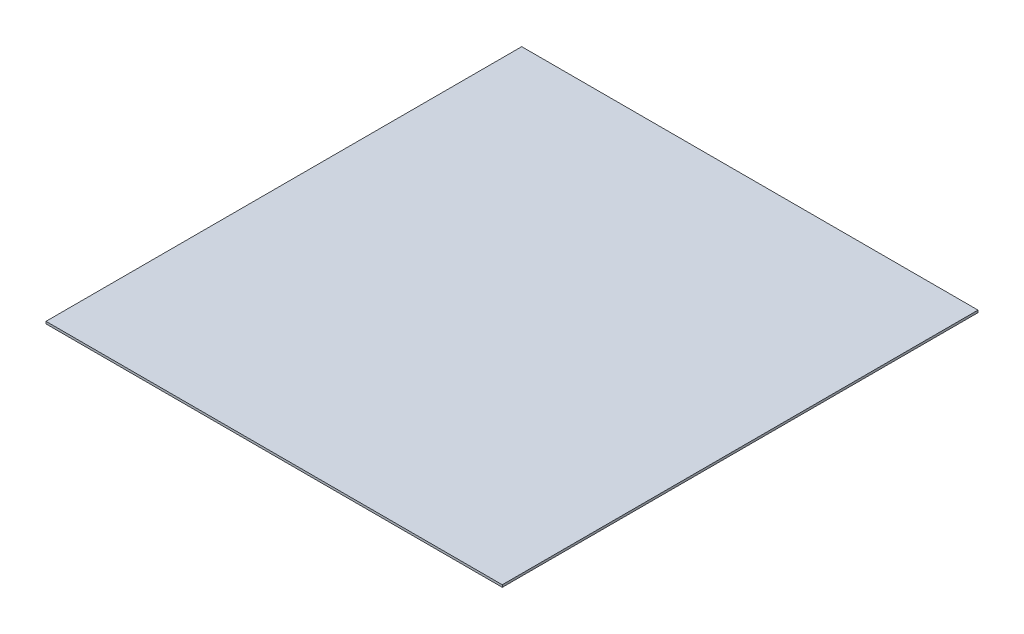
SolidWorks part; units mm, degrees
ref_plane "Front Plane" through (0, 0, 0) normal (0, 0, 1) x (1, 0, 0)
ref_plane "Top Plane" through (0, 0, 0) normal (0, 1, 0) x (1, 0, 0)
ref_plane "Right Plane" through (0, 0, 0) normal (1, 0, 0) x (0, 0, -1)
sketch "Sketch1" plane through (0, 0, 0) normal (0, 1, 0) x (1, 0, 0)
  line L1 (-176, 183.5) -> (176, 183.5)
  line L2 (-176, 183.5) -> (-176, -183.5)
  line L3 (-176, -183.5) -> (176, -183.5)
  line L4 (176, 183.5) -> (176, -183.5)
  line L5 (-176, 183.5) -> (176, -183.5) construction
  line L6 (-176, -183.5) -> (176, 183.5) construction
  point P0 (0, 0)
  dimension "D1" = 367
  dimension "D2" = 352
extrude "Boss-Extrude1" add sketch "Sketch1" along normal blind 1.75
sketch "Sketch2" plane through (0, 0, 0) normal (0, -1, 0) x (1, 0, 0)
  line L0 (0, 183.5) -> (0, -183.5) construction
  line L1 (-176, 183.5) -> (176, 183.5) construction
  line L2 (176, -183.5) -> (-176, -183.5) construction
  line L3 (-176, -183.5) -> (-176, 183.5) construction
  line L4 (-14, -183.5) -> (-176, -183.5)
  line L5 (-14, -183.5) -> (-14, -181.75)
  line L6 (-14, -181.75) -> (-176, -181.75)
  line L7 (-176, -183.5) -> (-176, -181.75)
  dimension "D1" = 1.75
  dimension "D2" = 14
extrude "Boss-Extrude3" add sketch "Sketch2" along normal blind 30
